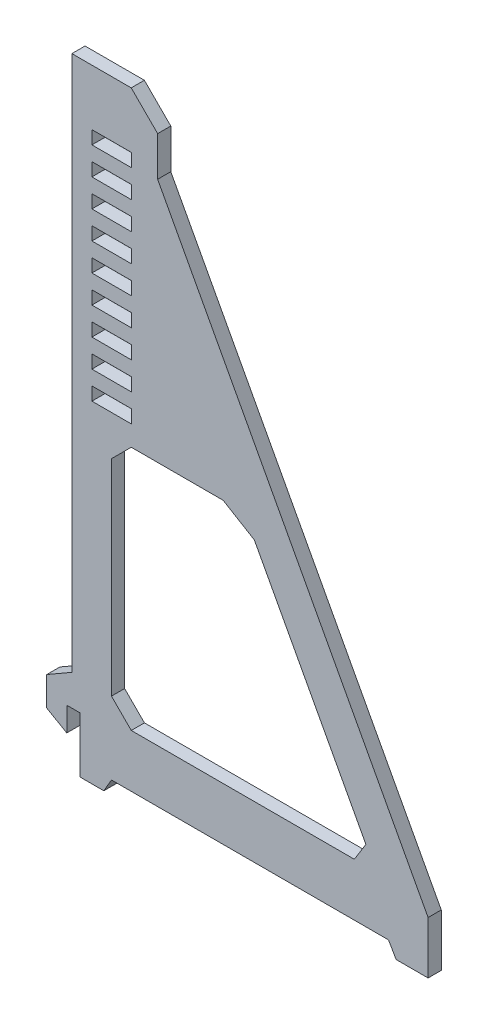
SolidWorks part; units mm, degrees
other "Markup1"
sketch "Sketch2" plane through (451.8627, 651.329, 334.843) normal (0.8622, 0.3297, 0.3847) x (0.4395, -0.109, -0.8916)
ref_plane "Front Plane" through (0, 0, 0) normal (0, 0, 1) x (1, 0, 0)
ref_plane "Top Plane" through (0, 0, 0) normal (0, 1, 0) x (1, 0, 0)
ref_plane "Right Plane" through (0, 0, 0) normal (1, 0, 0) x (0, 0, -1)
sketch "Sketch1" plane through (0, 0, 0) normal (0, 0, 1) x (1, 0, 0)
  line L1 (-15.6173, -25) -> (-13.1946, -25)
  line L2 (-15.6173, -25) -> (-15.6173, -22.8331)
  line L5 (-9.1173, 22.18) -> (-9.1173, 17.18)
  line L8 (-15.6173, 22.18) -> (-9.1173, 22.18)
  line L10 (-12.6173, -20) -> (7.4257, -20)
  line L11 (11.3827, -25) -> (11.3827, -21.0298)
  line L12 (-9.1173, 17.18) -> (11.3827, -21.0298)
  line L13 (-12.6173, -24) -> (8.3827, -24)
  line L14 (8.3827, -24) -> (8.9601, -25)
  line L15 (8.9601, -25) -> (9.8055, -25)
  line L16 (-12.6173, -1.41) -> (-2.548, -1.41) construction
  line L17 (-12.6173, -24) -> (-13.1946, -25)
  line L18 (8.9601, -25) -> (11.3827, -25)
  line L19 (-12.6173, -1.41) -> (-12.6173, -20)
  line L20 (-2.548, -1.41) -> (7.4257, -20)
  line L21 (-12.6173, -1.41) -> (-2.548, -1.41)
  line L22 (0.8565, -1.41) -> (27.1209, -1.41) construction
  line L23 (-15.6173, -18.4337) -> (-15.6173, 22.18)
  line L32 (-15.6173, -18.4337) -> (-17.5223, -19.5336)
  line L34 (-17.5223, -19.5336) -> (-17.5223, -21.7333)
  line L41 (-17.5223, -21.7333) -> (-15.6173, -22.8331)
  line L48 (-13.7123, -21.7333) -> (-13.7123, -19.5336) [skipped]
  line L49 (-14.6648, -18.9836) -> (-15.6173, -18.4337) [skipped]
  line L50 (-15.6173, -22.8331) -> (-14.6648, -22.2832) [skipped]
  point P0 (0, 0)
  dimension "D1" = 1
  dimension "D2" = 6.5
  dimension "D3" = 47.18
  dimension "D4" = 5
  dimension "D5" = 5
  dimension "D6" = 27
  dimension "D7" = 3
  dimension "D8" = 60
  dimension "D9" = 3
  dimension "D10" = 60
  dimension "D11" = 23.59
extrude "Boss-Extrude1" add sketch "Sketch1" along normal blind 25.4 contours L15 L18 L11 L12 L5 L8 L2 L1 L17 L13 L14 L19 L21 L20 L10
scale "Scale1" bodies to scale 101 scale about centroid uniform scaling yes scale factor 25.365591
sketch "Sketch3" plane through (0, 0, -309.443) normal (0, 0, -1) x (-1, 0, 0)
  line L1 (407.5134, -599.7995) -> (-634.8562, -599.7995)
  line L2 (407.5134, -599.7995) -> (407.5134, 673.4533)
  line L3 (407.5134, 673.4533) -> (-634.8562, 673.4533)
  line L4 (-634.8562, -599.7995) -> (-634.8562, 673.4533)
extrude "Cut-Extrude1" cut sketch "Sketch3" against normal blind 618.998
chamfer "Chamfer1" distance 50.8 angle 45 1 edges at (-65.0441, 656.7001, 322.199)
chamfer "Chamfer2" distance 38.1 angle 45 2 edges at (-153.8237, -413.2205, 322.199) (-153.8237, 58.3258, 322.199)
chamfer "Chamfer3" distance 40.64 angle 31 1 edges at (101.5889, 58.3258, 322.199)
chamfer "Chamfer4" distance 40.64 angle 60 1 edges at (354.5791, -413.2205, 322.199)
sketch "Sketch4" plane through (0, 0, 334.843) normal (0, 0, 1) x (1, 0, 0)
  line L0 (-229.9204, -540.0485) -> (-168.4685, -540.0485) construction
  line L1 (-214.3773, -540.0485) -> (-239.7773, -540.0485)
  line L2 (-214.3773, -540.0485) -> (-214.3773, -433.1771)
  line L3 (-214.3773, -433.1771) -> (-239.7773, -433.1771)
  line L4 (-239.7773, -540.0485) -> (-239.7773, -433.1771)
  dimension "D1" = 25.4
extrude "Cut-Extrude2" cut sketch "Sketch4" against normal blind 618.998 contours L2 L1 L4 L3
sketch "Sketch5" plane through (0, 0, 334.843) normal (0, 0, 1) x (1, 0, 0)
  line L0 (-191.4229, -540.0485) -> (-191.4229, 97.2375)
  line L1 (-214.3773, -540.0485) -> (-168.4685, -540.0485) construction
  line L2 (-191.4229, 150.5775) -> (-191.4229, 175.9775)
  line L3 (-191.4229, 97.2375) -> (-115.2229, 97.2375)
  line L4 (-191.4229, 97.2375) -> (-191.4229, 122.6375)
  line L5 (-191.4229, 122.6375) -> (-115.2229, 122.6375)
  line L6 (-115.2229, 97.2375) -> (-115.2229, 122.6375)
  line L7 (-191.4229, 150.5775) -> (-115.2229, 150.5775)
  line L8 (-115.2229, 150.5775) -> (-115.2229, 175.9775)
  line L9 (-191.4229, 175.9775) -> (-115.2229, 175.9775)
  line L10 (-191.4229, 203.9175) -> (-191.4229, 229.3175)
  line L11 (-191.4229, 203.9175) -> (-115.2229, 203.9175)
  line L12 (-115.2229, 203.9175) -> (-115.2229, 229.3175)
  line L13 (-191.4229, 229.3175) -> (-115.2229, 229.3175)
  line L14 (-191.4229, 257.2575) -> (-191.4229, 282.6575)
  line L15 (-191.4229, 257.2575) -> (-115.2229, 257.2575)
  line L16 (-115.2229, 257.2575) -> (-115.2229, 282.6575)
  line L17 (-191.4229, 282.6575) -> (-115.2229, 282.6575)
  line L18 (-191.4229, 310.5975) -> (-191.4229, 335.9975)
  line L19 (-191.4229, 310.5975) -> (-115.2229, 310.5975)
  line L20 (-115.2229, 310.5975) -> (-115.2229, 335.9975)
  line L21 (-191.4229, 335.9975) -> (-115.2229, 335.9975)
  line L22 (-191.4229, 363.9375) -> (-191.4229, 389.3375)
  line L23 (-191.4229, 363.9375) -> (-115.2229, 363.9375)
  line L24 (-115.2229, 363.9375) -> (-115.2229, 389.3375)
  line L25 (-191.4229, 389.3375) -> (-115.2229, 389.3375)
  line L26 (-191.4229, 417.2775) -> (-191.4229, 442.6775)
  line L27 (-191.4229, 417.2775) -> (-115.2229, 417.2775)
  line L28 (-115.2229, 417.2775) -> (-115.2229, 442.6775)
  line L29 (-191.4229, 442.6775) -> (-115.2229, 442.6775)
  line L30 (-201.6214, 424.1602) -> (-201.6214, 449.5602)
  line L31 (-201.6214, 424.1602) -> (-125.4214, 424.1602)
  line L32 (-125.4214, 424.1602) -> (-125.4214, 449.5602)
  line L33 (-201.6214, 449.5602) -> (-125.4214, 449.5602)
  dimension "D1" = 637.286
  dimension "D2" = 76.2
  dimension "D3" = 25.4
  dimension "D5" = 25.4
  dimension "D4" = 7
extrude "Cut-Extrude3" cut sketch "Sketch5" against normal through all contours L21 L18 L19 L20 | L13 L10 L11 L12 | L29 L28 L27 L26 | L25 L24 L23 L22 | L17 L16 L15 L14 | L9 L8 L7 L2 | L4 L5 L6 L3
pattern_linear "LPattern4" count 2 spacing 106.68 along (0, 1, 0) of "Cut-Extrude3"
sketch "Sketch6" plane through (-214.3773, 0, 0) normal (-1, 0, 0) x (0, 0, 1)
  line L0 (334.843, -433.1771) -> (309.555, -411.958)
  line L1 (309.555, -457.1856) -> (309.555, -401.3888) construction
  line L2 (309.555, -540.0485) -> (334.843, -540.0485) construction
  line L3 (334.843, -433.1771) -> (309.555, -433.1771)
  line L4 (309.555, -433.1771) -> (309.555, -540.0485) construction
  line L5 (309.555, -411.958) -> (309.555, -433.1771)
  dimension "D1" = 40
extrude "Cut-Extrude4" cut sketch "Sketch6" along normal blind 25.4
